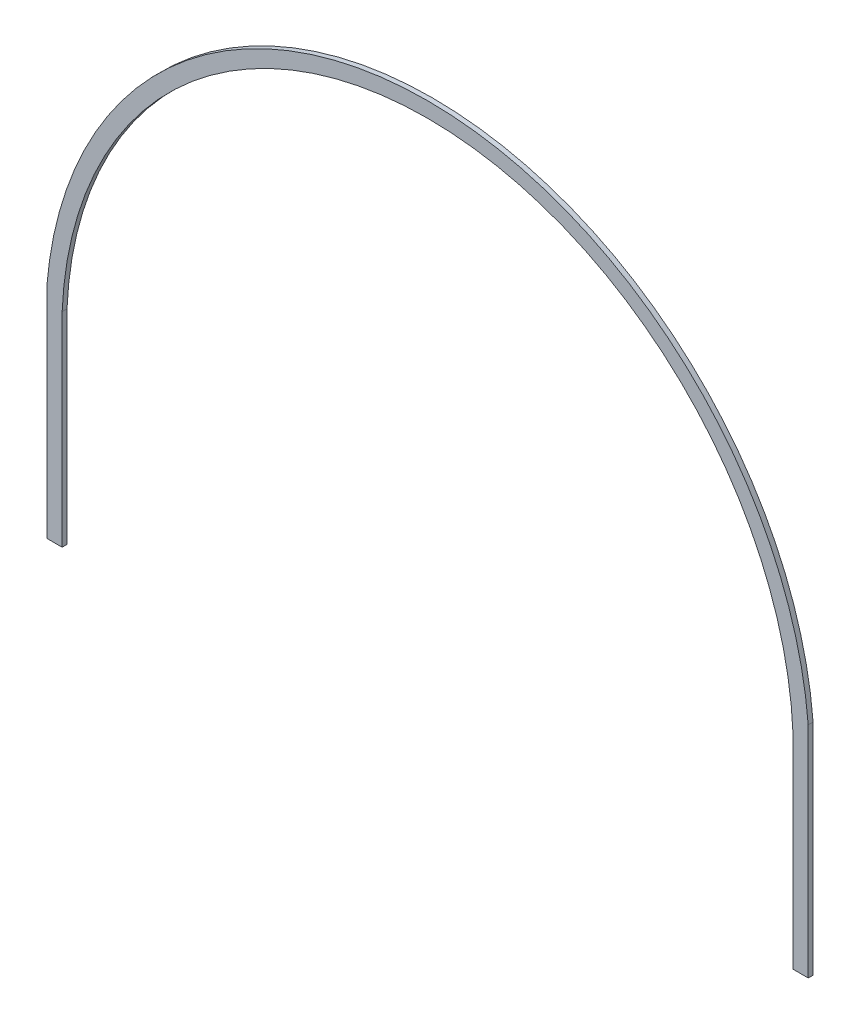
SolidWorks part; units mm, degrees
ref_plane "Plan de face" through (0, 0, 0) normal (0, 0, 1) x (1, 0, 0)
ref_plane "Plan de dessus" through (0, 0, 0) normal (0, 1, 0) x (1, 0, 0)
ref_plane "Plan de droite" through (0, 0, 0) normal (1, 0, 0) x (0, 0, -1)
sketch "Esquisse1" plane through (0, 0, 0) normal (0, 0, 1) x (1, 0, 0)
  line L2 (0, 0) -> (0, 187) construction
  line L3 (0, 187) -> (250, 187) construction
  line L4 (250, 0) -> (250, 187) construction
  line L6 (5, 0) -> (5, 67)
  line L8 (245, 0) -> (245, 67)
  line L14 (0, 0) -> (5, 0)
  line L15 (250, 0) -> (245, 0)
  line L16 (5, 67) -> (5, 187) construction
  line L17 (0, 0) -> (0, 72)
  line L18 (250, 0) -> (250, 72)
  line L19 (125, 182) -> (125, 187) construction
  arc A3 (0, 72) -> (250, 72) centre (125, 61.5652) cw
  arc A4 (245, 67) -> (5, 67) centre (125, 61.8913) ccw
extrude "Boss.-Extru.1" add sketch "Esquisse1" along normal blind 1.6
